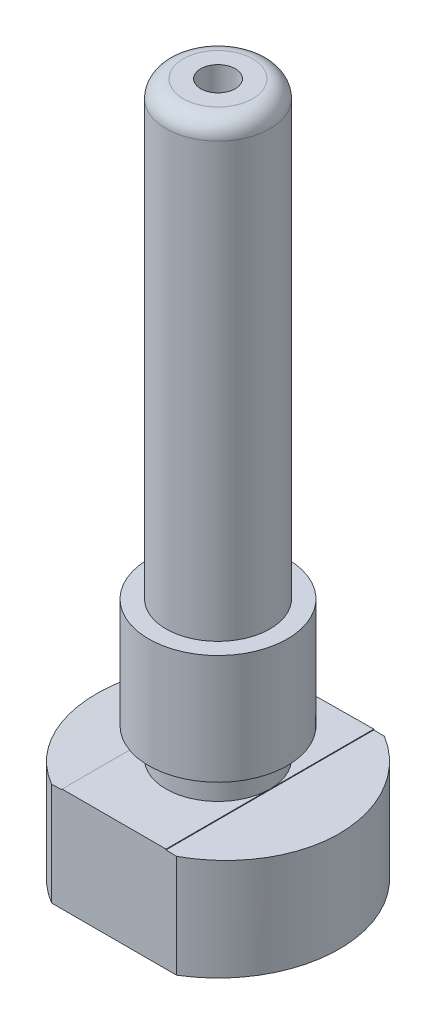
SolidWorks part; units mm, degrees
material "AISI Type A2 Tool Steel"
ref_plane "Front Plane" through (0, 0, 0) normal (0, 0, 1) x (1, 0, 0)
ref_plane "Top Plane" through (0, 0, 0) normal (0, 1, 0) x (1, 0, 0)
ref_plane "Right Plane" through (0, 0, 0) normal (1, 0, 0) x (0, 0, -1)
sketch "Sketch1" plane through (0, 0, 0) normal (0, 0, 1) x (1, 0, 0)
  line L0 (0, 0) -> (-3.5, 0)
  line L1 (-3.5, 0) -> (-3.5, 3)
  line L2 (-3.5, 3) -> (-1.5, 3)
  line L3 (-1.5, 3) -> (-1.5, 3.8332)
  line L4 (-1, 20) -> (0, 20)
  line L5 (0, 7) -> (0, 25.6531) construction
  line L6 (-1.5, 7) -> (-2, 7)
  line L7 (-1.5, 3.8332) -> (-2, 3.8332)
  line L8 (-2, 7) -> (-2, 3.8332)
  line L9 (-1.5, 7) -> (-1.5, 19.5)
  line L10 (0, 0) -> (0, 20)
  arc A0 (-1, 20) -> (-1.5, 19.5) centre (-1, 19.5) ccw
  dimension "D1" = 0.5
revolve "Revolve2" add sketch "Sketch1" angle 360 about L5
ref_plane "Plane1" through (0, 20, 0) normal (0, 1, 0) x (1, 0, 0)
sketch "Sketch2" plane through (0, 20, 0) normal (0, 1, 0) x (1, 0, 0)
  circle A0 centre (0, 0) radius 0.5
extrude "Cut-Extrude2" cut sketch "Sketch2" against normal through all
hole_wizard "Ø2.0mm Dowel Hole1" positions "Sketch5" profile "Sketch4" hole size "Ø2.0" standard "GB"
sketch "Sketch5" plane through (0, 0, 0) normal (0, -1, 0) x (-1, 0, 0)
  point P0 (0, 0)
sketch "Sketch4" plane through (0, 0, 0) normal (1, 0, 0) x (0, 0, -1)
  line L0 (0, 0) -> (0, 2.6009)
  line L1 (0, 2.6009) -> (1, 2)
  line L2 (1, 2) -> (1, 0)
  line L5 (1, 0) -> (0, 0)
  line L10 (0, 2.6009) -> (-1, 2) construction
  line L11 (0, -6.35) -> (0, 107.95) construction
  dimension "Hole Dia." = 2
  dimension "Hole Depth" = 2
  dimension "Drill Angle" = 118
sketch "Sketch6" plane through (0, 20, 0) normal (0, 1, 0) x (1, 0, 0)
  line L0 (1.8028, -3) -> (-1.8028, -3)
  line L1 (-1.8618, 2.9638) -> (1.8028, 3)
  circle A0 centre (0, 0) radius 3.5 construction
  arc A1 (-1.8618, 2.9638) -> (1.8028, 3) centre (0, 0) cw
  arc A2 (-1.8028, -3) -> (1.8028, -3) centre (0, 0) ccw
extrude "Cut-Extrude3" cut sketch "Sketch6" against normal through all
sketch "Sketch7" plane through (0, 0, 3) normal (0, 0, 1) x (1, 0, 0)
  line L0 (-6.315, 2.6274) -> (-6.0054, 3.4043)
  line L2 (-6.0054, 3.4043) -> (-1.5, 3.4166)
  line L3 (-1.5, 3.8332) -> (-1.5, 3) construction
  line L4 (-1.5, 3.4166) -> (-1.5, 2.979)
  line L5 (5.5655, 2.7108) -> (5.5655, 3.4166)
  line L6 (5.5655, 3.4166) -> (1.5, 3.4166)
  line L7 (1.5, 3) -> (1.5, 3.8332) construction
  line L8 (1.5, 3.4166) -> (1.5, 2.979)
  arc A0 (-1.5, 2.979) -> (-6.315, 2.6274) centre (0, -50.7) ccw
  arc A1 (5.5655, 2.7108) -> (1.5, 2.979) centre (0, -50.7) ccw
extrude "Cut-Extrude4" cut sketch "Sketch7" against normal blind 10
